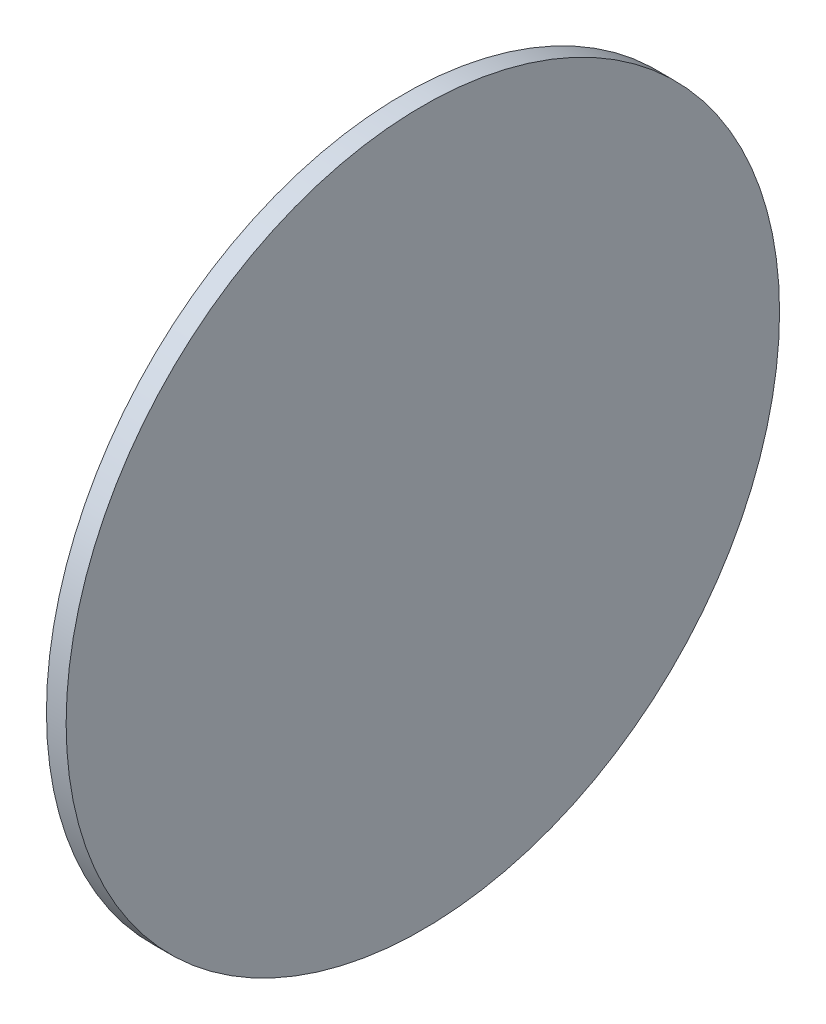
SolidWorks part; units mm, degrees
ref_plane "Ebene vorne" through (0, 0, 0) normal (0, 0, 1) x (1, 0, 0)
ref_plane "Ebene oben" through (0, 0, 0) normal (0, 1, 0) x (1, 0, 0)
ref_plane "Ebene rechts" through (0, 0, 0) normal (1, 0, 0) x (0, 0, -1)
sketch "Sketch1" plane through (0, 0, 0) normal (1, 0, 0) x (0, 0, -1)
  circle A0 centre (0, 0) radius 72.5
  dimension "D1" = 145
extrude "Boss-Extrude1" add sketch "Sketch1" along normal blind 4
